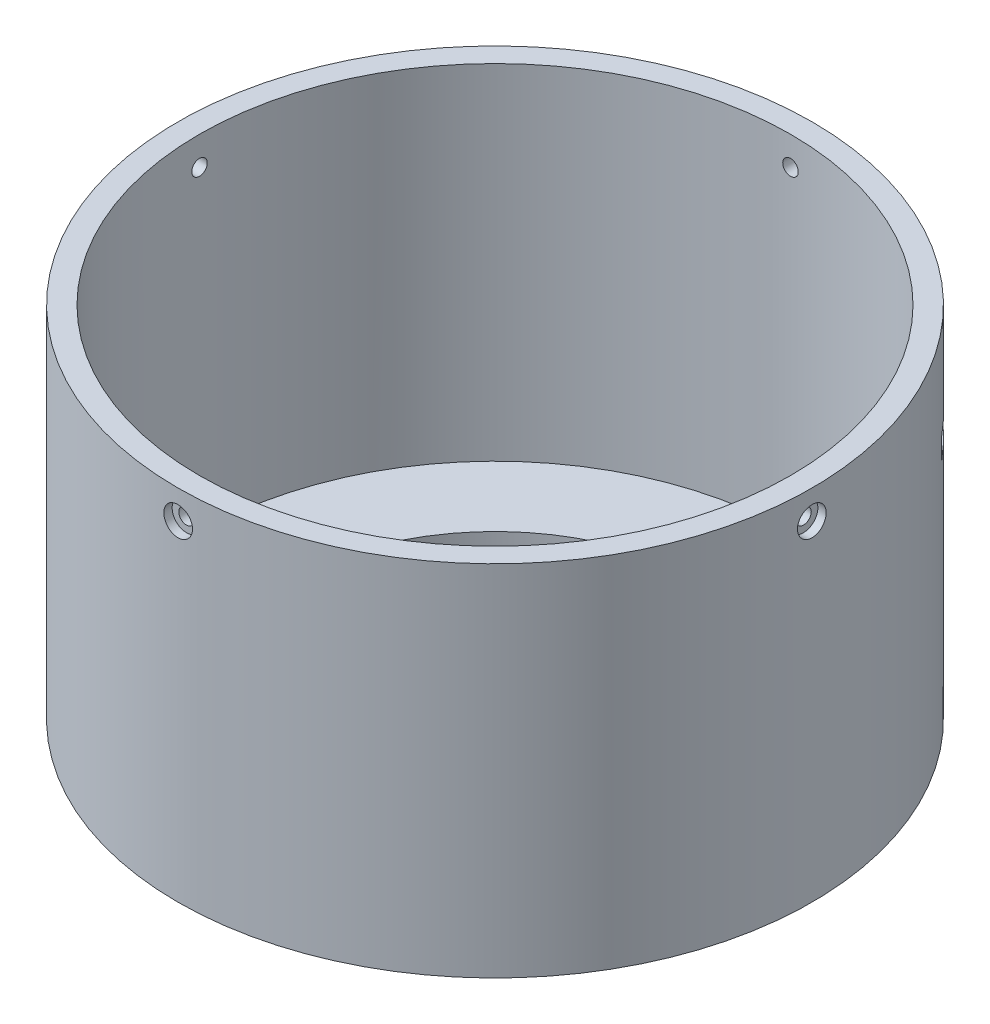
SolidWorks part; units mm, degrees
ref_plane "Piano frontale" through (0, 0, 0) normal (0, 0, 1) x (1, 0, 0)
ref_plane "Piano superiore" through (0, 0, 0) normal (0, 1, 0) x (1, 0, 0)
ref_plane "Piano destro" through (0, 0, 0) normal (1, 0, 0) x (0, 0, -1)
sketch "Schizzo1" plane through (0, 0, 0) normal (0, 1, 0) x (1, 0, 0)
  circle A0 centre (0, 0) radius 110.5
  circle A1 centre (0, 0) radius 103
  dimension "D1" = 221
  dimension "D2" = 7.5
extrude "Estrusione-Estrusione1" add sketch "Schizzo1" along normal blind 125
hole_wizard "Foro lamato per Bullone M12 a testa esagonale (Classe superiore)-1" positions "Schizzo3D1" profile "Schizzo3" counterbore size "M12" standard "DIN"
sketch3d "Schizzo3D1"
  line L0 (0, 0, 0) -> (0, 115, 0) construction
  line L2 (0, 115, 110.5) -> (0, 115, -110.5) construction
  line L4 (-110.5, 115, 0) -> (110.5, 115, 0) construction
  circle A0 centre (0, 115, 0) radius 110.5
  circle A1 centre (0, 125, 0) radius 110.5 construction
  point P0 (0, 115, 110.5)
  point P2 (110.5, 115, 0)
  point P4 (0, 115, -110.5)
  point P6 (-110.5, 115, 0)
  point P15 (0, 225.5, 0)
  point P19 (0, 235.5, 0)
  dimension "D1" = 115
sketch "Schizzo3" plane through (0, 115, 110.5) normal (1, 0, 0) x (0, -1, 0)
  line L0 (0, 0) -> (0, 9.7223)
  line L1 (0, 9.7223) -> (2.7, 8.1)
  line L2 (2.7, 8.1) -> (2.7, 3)
  line L3 (2.7, 3) -> (5, 3)
  line L4 (5, 3) -> (5, 0)
  line L5 (5, 0) -> (0, 0)
  line L10 (0, 9.7223) -> (-2.7, 8.1) construction
  line L11 (0, -6.35) -> (0, 107.95) construction
  dimension "Hole Dia." = 5.4
  dimension "Hole Depth" = 8.1
  dimension "C'Bore Dia." = 10
  dimension "C'Bore Depth" = 3
  dimension "Drill Angle" = 118
sketch "Schizzo4" plane through (0, 0, 0) normal (0, -1, 0) x (1, 0, 0)
  circle A0 centre (0, 0) radius 103
  circle A1 centre (0, 0) radius 73
  circle A2 centre (0, 0) radius 103 construction
  dimension "D1" = 30
extrude "Estrusione-Estrusione2" add sketch "Schizzo4" against normal blind 5
hole_wizard "Foro per Vite M6-1" positions "Schizzo5" profile "Schizzo6" hole size "M6" standard "DIN" end condition through all
sketch "Schizzo5" plane through (0, 5, 0) normal (0, 1, 0) x (1, 0, 0)
  circle A0 centre (0, 0) radius 88
  circle A1 centre (0, 0) radius 73 construction
  point P4 (-88, 0)
  point P6 (88, 0)
  point P8 (0, 88)
  point P10 (0, -88)
  dimension "D1" = 15
sketch "Schizzo6" plane through (0, 5, 88) normal (1, 0, 0) x (0, 0, 1)
  line L0 (0, 0) -> (0, 5)
  line L1 (0, 5) -> (3.3, 5)
  line L2 (3.3, 5) -> (3.3, 0)
  line L5 (3.3, 0) -> (0, 0)
  line L11 (0, -6.35) -> (0, 107.95) construction
  dimension "Thru Hole Dia." = 6.6
  dimension "Thru Hole Depth" = 5
ref_plane "Piano1" through (78.1353, 0, -78.1353) normal (0.7071, 0, -0.7071) x (0, -1, 0)
sketch "Schizzo7" plane through (78.1353, 0, -78.1353) normal (0.7071, 0, -0.7071) x (0, -1, 0)
  line L0 (0, 0) -> (-85, 0) construction
  line L1 (-92.25, 10) -> (-85, 10)
  line L2 (-92.25, 10) -> (-92.25, -10)
  line L3 (-92.25, -10) -> (-85, -10)
  line L4 (-85, 10) -> (-85, -10)
  dimension "D1" = 7.25
  dimension "D2" = 20
  dimension "D3" = 85
extrude "Taglio-Estrusione1" cut sketch "Schizzo7" against normal blind 10
